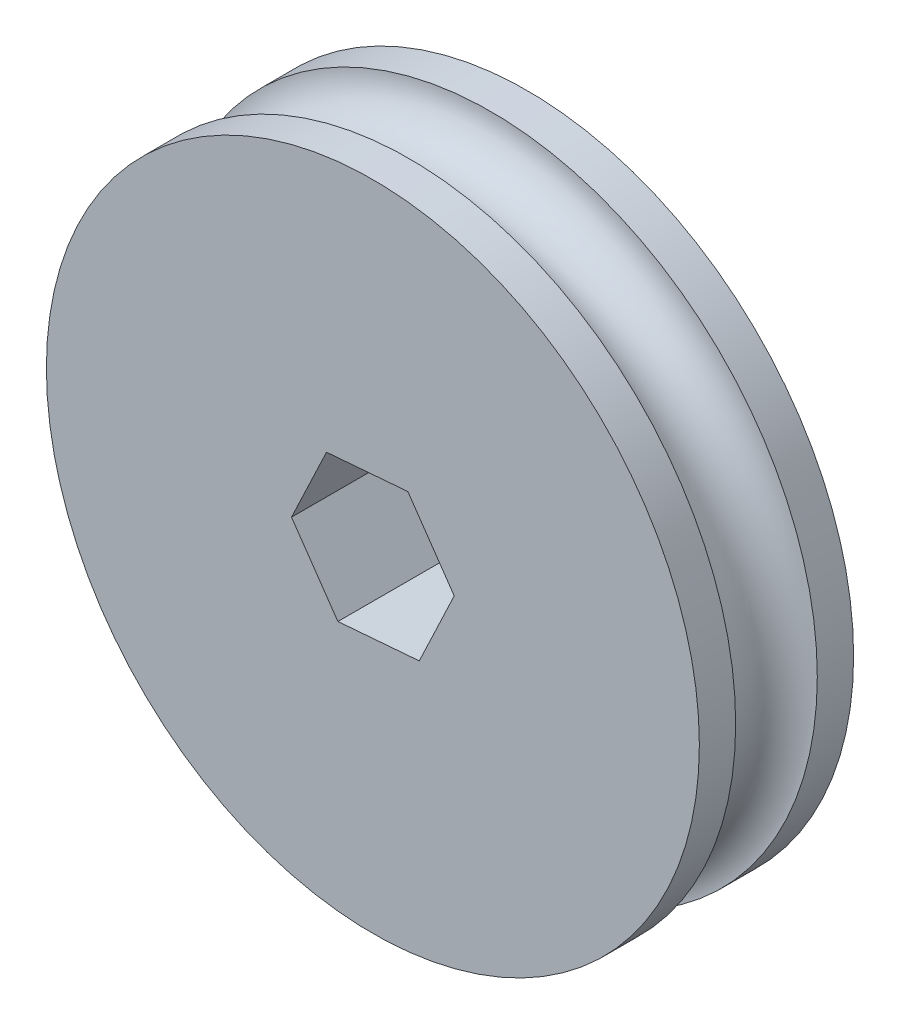
SolidWorks part; units mm, degrees
ref_plane "Front Plane" through (0, 0, 0) normal (0, 0, 1) x (1, 0, 0)
ref_plane "Top Plane" through (0, 0, 0) normal (0, 1, 0) x (1, 0, 0)
ref_plane "Right Plane" through (0, 0, 0) normal (1, 0, 0) x (0, 0, -1)
sketch "Sketch1" plane through (0, 0, 0) normal (0, 1, 0) x (1, 0, 0)
  line L1 (12.7, 0) -> (25.4, 0)
  line L2 (0, 0) -> (0, 12) construction
  line L3 (12.7, 12) -> (25.4, 12)
  line L8 (12.7, 0) -> (12.7, 12)
  line L9 (25.4, 12) -> (25.4, 9.175)
  line L10 (25.4, 2.825) -> (25.4, 0)
  arc A0 (25.4, 9.175) -> (25.4, 2.825) centre (25.4, 6) ccw
  dimension "D3" = 6.35
  dimension "D4" = 12.7
  dimension "D1" = 12
  dimension "D2" = 25.4
revolve "Revolve1" add sketch "Sketch1" angle 360 about L2
sketch "Sketch2" plane through (0, 0, 0) normal (0, 0, 1) x (1, 0, 0)
  line L1 (3.6094, -5.2255) -> (6.3301, 0.5131)
  line L2 (6.3301, 0.5131) -> (2.7207, 5.7386)
  line L3 (2.7207, 5.7386) -> (-3.6094, 5.2255)
  line L4 (-3.6094, 5.2255) -> (-6.3301, -0.5131)
  line L5 (-6.3301, -0.5131) -> (-2.7207, -5.7386)
  line L6 (-2.7207, -5.7386) -> (3.6094, -5.2255)
  circle A0 centre (0, 0) radius 5.5 construction
  circle A1 centre (0, 0) radius 12.7 construction
  circle A2 centre (0, 0) radius 12.7
  dimension "D1" = 11
extrude "Boss-Extrude1" add sketch "Sketch2" against normal up to surface (12 mm away) up to face at (12.7, 0, -12)
